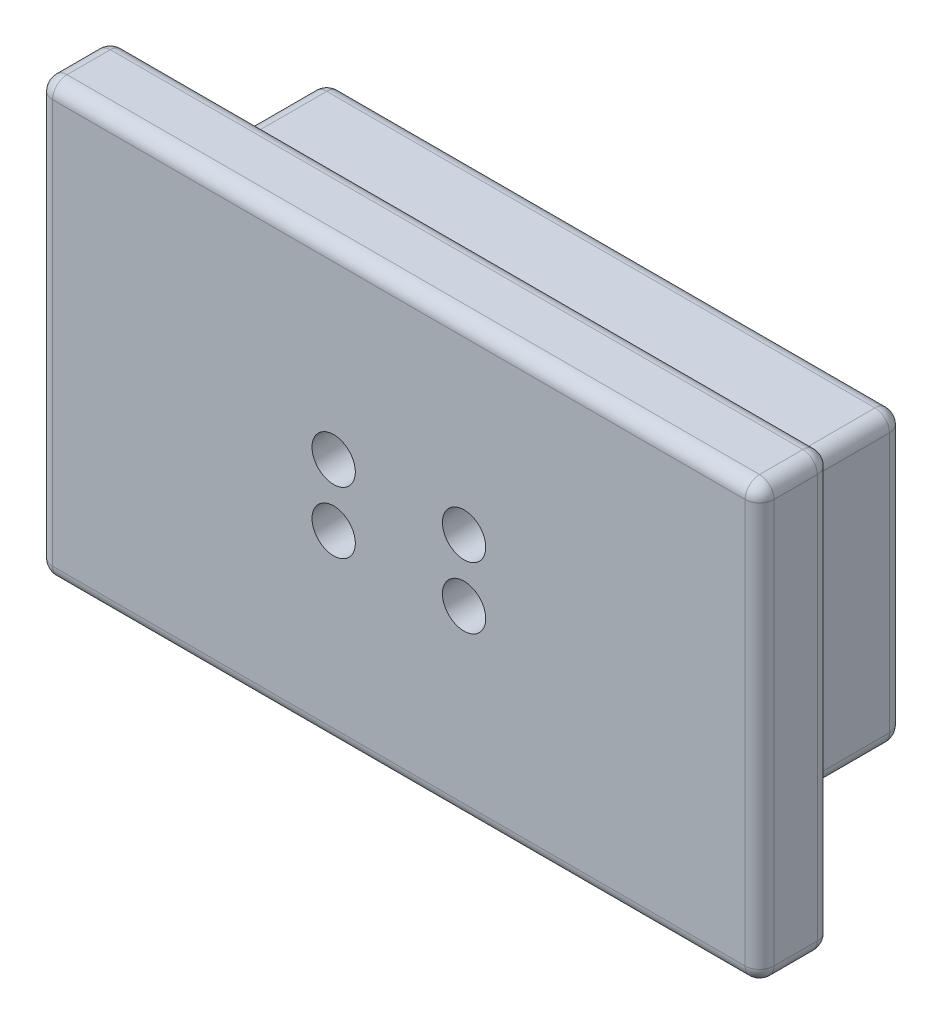
SolidWorks part; units mm, degrees
material "热轧圆钢 45"
ref_plane "前视基准面" through (0, 0, 0) normal (0, 0, 1) x (1, 0, 0)
ref_plane "上视基准面" through (0, 0, 0) normal (0, 1, 0) x (1, 0, 0)
ref_plane "右视基准面" through (0, 0, 0) normal (1, 0, 0) x (0, 0, -1)
sketch "草图1" plane through (0, 0, 0) normal (0, 0, 1) x (1, 0, 0)
  line L1 (-20, 10) -> (20, 10)
  line L2 (-20, 10) -> (-20, -10)
  line L3 (-20, -10) -> (20, -10)
  line L4 (20, 10) -> (20, -10)
  line L5 (-20, 10) -> (20, -10) construction
  line L6 (-20, -10) -> (20, 10) construction
  point P0 (0, 0)
  dimension "D1" = 20
  dimension "D2" = 40
extrude "凸台-拉伸1" add sketch "草图1" along normal blind 10
sketch "草图2" plane through (0, 0, 10) normal (0, 0, 1) x (1, 0, 0)
  line L1 (-25, 15) -> (25, 15)
  line L2 (-25, 15) -> (-25, -15)
  line L3 (-25, -15) -> (25, -15)
  line L4 (25, 15) -> (25, -15)
  line L5 (-25, 15) -> (25, -15) construction
  line L6 (-25, -15) -> (25, 15) construction
  point P0 (0, 0)
  dimension "D1" = 30
  dimension "D2" = 50
extrude "凸台-拉伸2" add sketch "草图2" along normal blind 5
fillet "圆角1" radius 1 24 edges at (0, 15, 15) (25, 0, 15) (25, 15, 12.5) (0, -15, 15) (25, -15, 12.5) (-25, 15, 12.5) (-25, 0, 15) (-25, -15, 12.5) (-20, -10, 5) (20, -10, 5) (20, 10, 5) (-20, 10, 5) (-20, 0, 10) (0, 10, 10) (20, 0, 10) (0, -10, 10) (0, 15, 10) (-25, 0, 10) (0, -15, 10) (25, 0, 10) (0, 10, 0) (-20, 0, 0) (0, -10, 0) (20, 0, 0)
sketch "草图3" plane through (0, 0, 0) normal (0, 0, -1) x (-1, 0, 0)
  line L0 (-19, -9) -> (19, 9) construction
  line L1 (-19, 9) -> (19, -9) construction
  circle A0 centre (-4.5187, -2.1404) radius 1.5
  circle A1 centre (4.5187, 2.1404) radius 1.5
  circle A2 centre (-4.5187, 2.1404) radius 1.5
  circle A3 centre (4.5187, -2.1404) radius 1.5
  dimension "D1" = 3
  dimension "D3" = 3
  dimension "D5" = 3
  dimension "D6" = 3
  dimension "D2" = 5
  dimension "D4" = 5
  dimension "D7" = 5
  dimension "D8" = 5
extrude "切除-拉伸1" cut sketch "草图3" against normal through all
